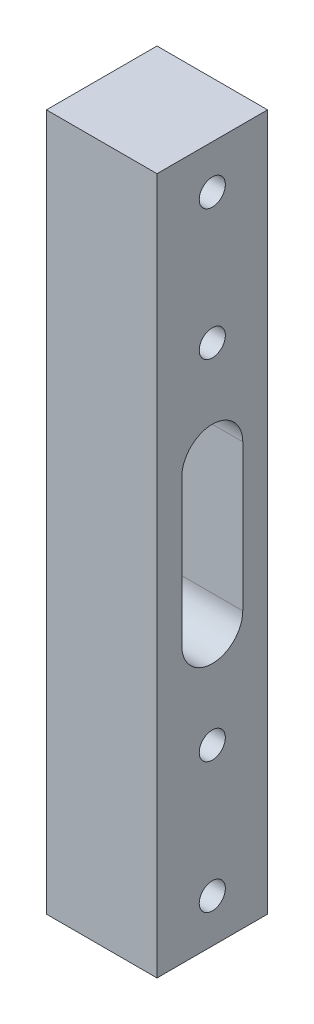
SolidWorks part; units mm, degrees
ref_plane "Front Plane" through (0, 0, 0) normal (0, 0, 1) x (1, 0, 0)
ref_plane "Top Plane" through (0, 0, 0) normal (0, 1, 0) x (1, 0, 0)
ref_plane "Right Plane" through (0, 0, 0) normal (1, 0, 0) x (0, 0, -1)
ref_plane "Plane1" through (572.9524, -103.7335, -119.474) normal (1, 0, 0) x (0, 0, 1)
sketch "Sketch1" plane through (572.9524, -103.7335, -119.474) normal (1, 0, 0) x (0, 0, 1)
  line L0 (-165.5779, 189.3701) -> (-165.5779, 161.2754) construction
  line L1 (-171.9279, 189.3701) -> (-159.2279, 189.3701)
  line L2 (-171.9279, 189.3701) -> (-171.9279, 109.3701)
  line L3 (-171.9279, 109.3701) -> (-159.2279, 109.3701)
  line L4 (-159.2279, 189.3701) -> (-159.2279, 109.3701)
  line L5 (-162.0779, 157.7754) -> (-162.0779, 140.9649)
  line L6 (-162.0779, 149.3701) -> (-159.2279, 149.3701) construction
  line L7 (-169.0779, 157.7754) -> (-169.0779, 140.9649)
  line L8 (-165.5779, 137.4649) -> (-165.5779, 109.3701) construction
  circle A1 centre (-165.5779, 169.3701) radius 1.5
  circle A2 centre (-165.5779, 184.3701) radius 1.5
  circle A4 centre (-165.5779, 114.3701) radius 1.5
  circle A5 centre (-165.5779, 129.3701) radius 1.5
  arc A6 (-162.0779, 157.7754) -> (-169.0779, 157.7754) centre (-165.5779, 157.7754) ccw
  arc A7 (-169.0779, 140.9649) -> (-162.0779, 140.9649) centre (-165.5779, 140.9649) ccw
  dimension "D1" = 15
  dimension "D2" = 5
  dimension "D5" = 3
  dimension "D6" = 3
  dimension "D7" = 15
  dimension "D8" = 5
  dimension "D10" = 7
  dimension "D3" = 80
  dimension "D4" = 12.7
extrude "Boss-Extrude1" add sketch "Sketch1" along normal blind 12.7
